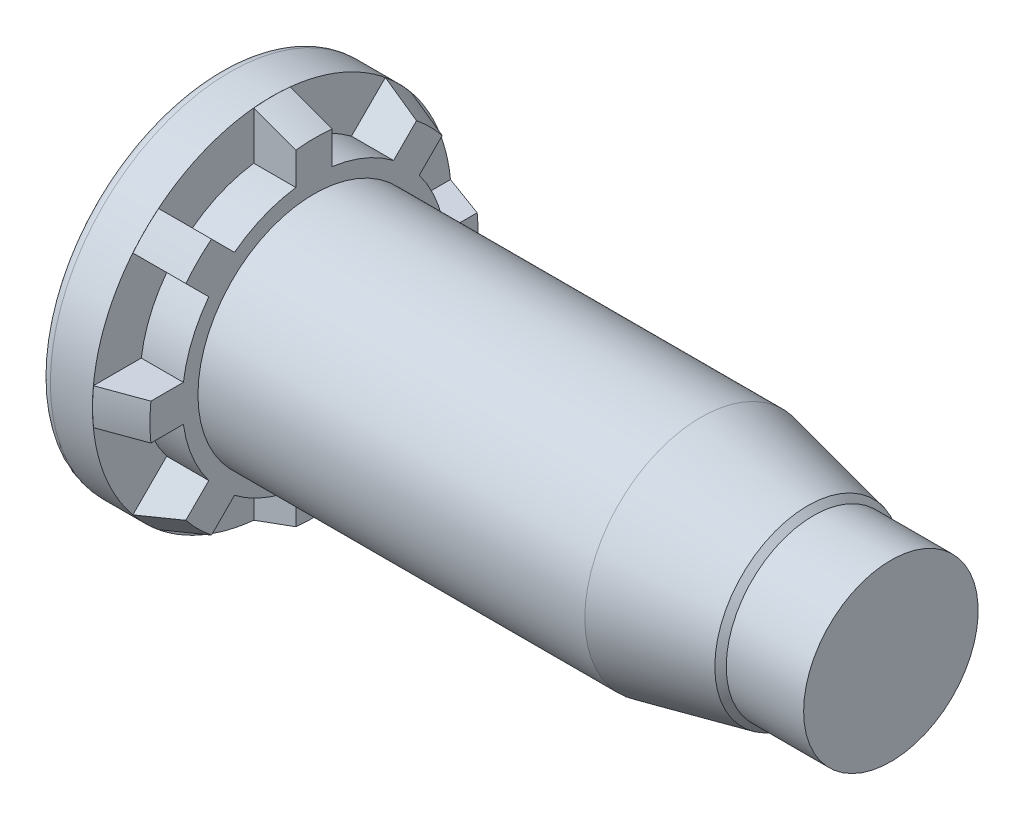
SolidWorks part; units mm, degrees
revolve "BaseBody" add sketch "BodySke" angle 360 about L6
sketch "BodySke" plane through (0, 0, 0) normal (0, 0, 1) x (1, 0, 0)
  line L0 (-2.159, 6.9342) -> (-2.159, 0)
  line L1 (1.7272, 6.7357) -> (1.7272, 4.7625)
  line L2 (0.0025, 7.3635) -> (1.7272, 6.7357)
  line L3 (1.7272, 4.7625) -> (17.6022, 4.7625)
  line L4 (17.6022, 4.7625) -> (21.99, 3.8163)
  line L5 (25.4, 0) -> (-2.159, 0)
  line L6 (0, 0) -> (50.554, 0) construction
  line L7 (22.225, 3.5814) -> (25.4, 3.5814)
  line L8 (22.225, 3.5814) -> (21.99, 3.8163)
  line L9 (-1.7272, 7.366) -> (0, 7.366)
  line L10 (0.0025, 7.3635) -> (0, 7.3635)
  line L11 (1.5875, 19.05) -> (1.5875, -3.175) construction
  line L12 (0, 7.3635) -> (0, 7.366)
  line L13 (25.4, 3.5814) -> (25.4, 0)
  arc A0 (-2.159, 6.9342) -> (-1.7272, 7.366) centre (-1.7272, 6.9342) cw
  dimension "Fillet_rad" = 0.4318
  dimension "T_dim" = 2.159
  dimension "H_dia" = 14.732
  dimension "D2" = 0.0025
  dimension "D3" = 0.0025
  dimension "Advance" = 1.5875
  dimension "D1" = 20
  dimension "Clinch_ht" = 1.7272
  dimension "Dog_len" = 3.175
  dimension "Length" = 25.4
  dimension "Dog_dia" = 7.1628
  dimension "D4" = 45
  dimension "Diameter" = 9.525
  dimension "Thread_trans" = 4.6228
  dimension "Minor_dia" = 7.6327
cosmetic thread "ThreadCosmetic" [suppressed] parameters "Thread_length"=18.0531, "Thread_minor"=7.6327
ref_plane "Plane1" through (0, 0, 0) normal (0, 0, 1) x (1, 0, 0)
ref_plane "Plane2" through (0, 0, 0) normal (0, 1, 0) x (1, 0, 0)
ref_plane "Plane3" through (0, 0, 0) normal (1, 0, 0) x (0, 0, -1)
sketch "ThdSchSke" plane through (0, 0, 0) normal (0, 0, 1) x (1, 0, 0)
  line L0 (3.937, -3.8163) -> (3.2745, -4.7625)
  line L1 (3.937, -3.8163) -> (4.5995, -4.7625)
  line L2 (4.5995, -4.7625) -> (4.5995, -5.9531)
  line L3 (-3.175, 0) -> (5.1513, 0) construction
  line L4 (0, -7.366) -> (0, 7.366) construction
  line L5 (4.5995, -5.9531) -> (3.2745, -5.9531)
  line L6 (3.2745, -5.9531) -> (3.2745, -4.7625)
  line L7 (21.9888, 6.5809) -> (21.9888, 1.1961) construction
  dimension "Thread_minor" = 7.6327
  dimension "Diameter" = 9.525
  dimension "Start" = 3.937
revolve "ThreadSchematic" [suppressed] cut sketch "ThdSchSke" angle 360 about L3
pattern_linear "ThdSchPat" [suppressed]
sketch "RibCutSke" plane through (1.7272, 1.7944, -0.091) normal (1, 0, 0) x (0, 0, -1)
  line L0 (0.6541, 3.5675) -> (0.6541, 5.5338)
  line L1 (3.1736, 2.5238) -> (4.5641, 3.9142)
  line L2 (0.6541, 2.9095) -> (0.6541, 2.4006) construction
  line L3 (-0.091, -1.7944) -> (-0.091, 5.0239) construction
  line L4 (-0.091, -1.7944) -> (0.6541, 2.9095) construction
  line L5 (-0.091, -1.7944) -> (2.7084, 2.0585) construction
  line L6 (2.7084, 2.0585) -> (2.3536, 1.7038) construction
  arc A1 (3.1736, 2.5238) -> (0.6541, 3.5675) centre (-0.091, -1.7944) ccw
  arc A2 (4.5641, 3.9142) -> (0.6541, 5.5338) centre (-0.091, -1.7944) ccw
  circle A3 centre (-0.091, -1.7944) radius 6.7357 construction
  circle A4 centre (-0.091, -1.7944) radius 4.7625 construction
  dimension "Rib_root_half_angle" = 9
  dimension "Rib_root_gap_angle" = 27
  dimension "Angle" = 45
extrude "RibCut" cut sketch "RibCutSke" against normal blind 1.7272
pattern_circular "RibCutsPat" count 8 every 45 about axis through (0, 0, 0) along (1, 0, 0) of "RibCut"
equation "' \"Length@BodySke\" = 1"
equation "' \"H_dia@BodySke\" = 0.58"
equation "' \"Start@ThdSchSke\" = 0.155"
equation "' \"T_dim@BodySke\" = 0.085"
equation "' \"Dog_dia@BodySke\" = 0.282"
equation "' \"Dog_len@BodySke\" = 0.125"
equation "' \"Thread_trans@BodySke\" = 0.182"
equation "' \"Diameter@BodySke\" = 0.375"
equation "' \"Minor_dia@BodySke\" =  0.3005"
equation "' \"Minor_dia@BodySke\" = 0.3005"
equation "' \"Advance@BodySke\" = 0.0625"
equation "\"Fillet_rad@BodySke\" =  \"T_dim@BodySke\" * 0.2"
equation "\"Clinch_ht@BodySke\" = \"T_dim@BodySke\" * 0.8"
equation "\"Num_ribs@RibCutsPat\" = 8"
equation "\"Angle@RibCutSke\" =\"Angle@RibCutsPat\""
equation "\"Rib_root_half_angle@RibCutSke\" = \"Angle@RibCutSke\" / 5"
equation "\"Rib_root_gap_angle@RibCutSke\" = \"Angle@RibCutSke\" - (2 * \"Rib_root_half_angle@RibCutSke\" )"
equation "\"Rib_root_dia@RibCutSke\" = \"Diameter@BodySke\""
equation "\"Inner_dia@RibCutSke\" = \"Diameter@BodySke\" + ( \"H_dia@BodySke\" - \"Diameter@BodySke\" ) / 4"
equation "\"Outer_dia@RibCutSke\" = \"H_dia@BodySke\""
equation "\"Depth@RibCut\" = \"Clinch_ht@BodySke\""
equation "\"Thread_length@ThreadCosmetic\" = \"Length@BodySke\" - \"Start@ThdSchSke\"  - \"Dog_len@BodySke\"  - ( \"Minor_dia@BodySke\" - \"Dog_dia@BodySke\" ) / 2"
equation "\"Thread_minor@ThreadCosmetic\" = \"Minor_dia@BodySke\""
equation "\"Thread_minor@ThdSchSke\" = \"Minor_dia@BodySke\""
equation "\"Diameter@ThdSchSke\" = \"Diameter@BodySke\""
equation "\"Overcut@ThdSchSke\" = \"Diameter@BodySke\" * 1.25"
equation "\"Num_threads@ThdSchPat\" = int( \"Thread_length@ThreadCosmetic\" / \"Advance@BodySke\" + 0.999 )  + 1"
equation "\"Advance@ThdSchPat\" = \"Thread_length@ThreadCosmetic\" /  (\"Num_threads@ThdSchPat\" - 1) 'relax it"
equation "\"Num_threads@ThdSchPat\" = \"Num_threads@ThdSchPat\" - sgn( \"Num_threads@ThdSchPat\" - 1) '---chamfered tips only---"
